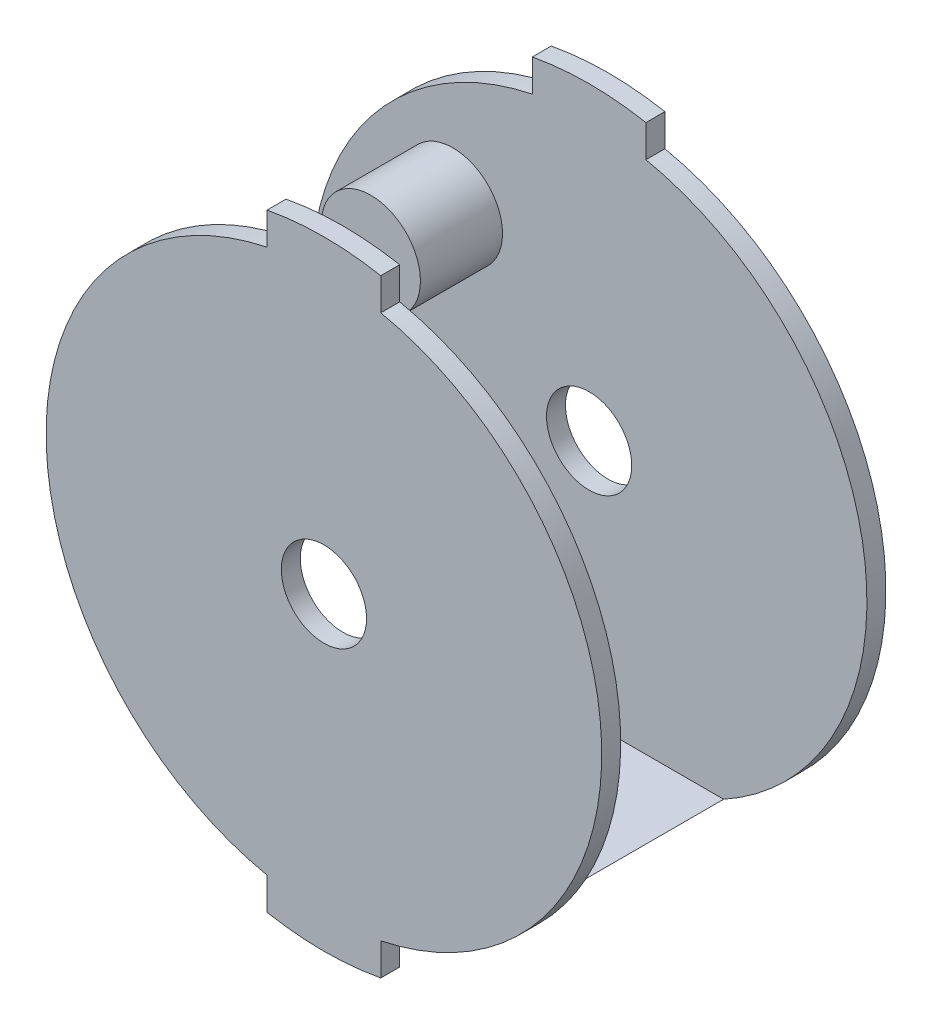
SolidWorks part; units mm, degrees
ref_plane "Front Plane" through (0, 0, 0) normal (0, 0, 1) x (1, 0, 0)
ref_plane "Top Plane" through (0, 0, 0) normal (0, 1, 0) x (1, 0, 0)
ref_plane "Right Plane" through (0, 0, 0) normal (1, 0, 0) x (0, 0, -1)
sketch "Sketch1" plane through (0, 0, 0) normal (0, 0, 1) x (1, 0, 0)
  line L0 (-2.286, 12.2343) -> (-2.286, 10.9397)
  line L1 (2.286, 12.2343) -> (2.286, 10.9397)
  line L2 (2.286, 12.2343) -> (-2.286, -12.2343) construction
  line L3 (-2.286, -10.9397) -> (-2.286, -12.2343)
  line L4 (2.286, -10.9397) -> (2.286, -12.2343)
  arc A0 (2.286, -10.9397) -> (2.286, 10.9397) centre (0, 0) ccw
  circle A1 centre (0, 0) radius 1.7145
  arc A2 (-2.286, -12.2343) -> (2.286, -12.2343) centre (0, 0) ccw
  arc A3 (2.286, 12.2343) -> (-2.286, 12.2343) centre (0, 0) ccw
  arc A4 (-2.286, 10.9397) -> (-2.286, -10.9397) centre (0, 0) ccw
  dimension "D1" = 22.352
  dimension "D2" = 3.429
  dimension "D3" = 4.572
  dimension "D4" = 24.892
extrude "Boss-Extrude1" add sketch "Sketch1" along normal blind 11.43
sketch "Sketch2" plane through (0, 0, 0) normal (1, 0, 0) x (0, 0, -1)
  line L0 (-11.43, 1.7145) -> (-11.43, -1.7145) construction
  line L1 (-10.668, 11.176) -> (-0.762, 11.176)
  line L2 (-10.668, 11.176) -> (-10.668, 13.716)
  line L3 (-10.668, 13.716) -> (-0.762, 13.716)
  line L4 (-0.762, 11.176) -> (-0.762, 13.716)
  line L5 (-10.668, 11.176) -> (-0.762, 13.716) construction
  line L6 (-10.668, 13.716) -> (-0.762, 11.176) construction
  point P0 (-5.715, 12.446)
  dimension "D1" = 11.176
  dimension "D2" = 0.762
  dimension "D3" = 0.762
  dimension "D4" = 2.54
ref_axis "Axis1" through (0, 0, 11.43) along (0, 0, -1)
revolve "Cut-Revolve1" cut sketch "Sketch2" angle 360 about axis through (0, 0, 11.43) along (0, 0, -1)
sketch "Sketch4" plane through (0, 0, 0) normal (1, 0, 0) x (0, 0, -1)
  line L0 (-0.762, 11.176) -> (-10.668, 11.176) construction
  line L1 (-0.762, 11.176) -> (-10.668, 11.176)
  line L2 (-0.762, 11.176) -> (-0.762, -9.779)
  line L3 (-0.762, -9.779) -> (-10.668, -9.779)
  line L4 (-10.668, 11.176) -> (-10.668, -9.779)
  line L6 (-10.668, 10.9397) -> (-10.668, 11.176) construction
  line L7 (-0.762, 11.176) -> (-0.762, 10.9397) construction
  line L8 (-0.762, -10.9397) -> (-0.762, -11.176) construction
  line L9 (-0.762, -11.176) -> (-10.668, -11.176)
  line L10 (-0.762, -11.176) -> (-0.762, -10.541)
  line L11 (-0.762, -10.541) -> (-10.668, -10.541)
  line L12 (-10.668, -11.176) -> (-10.668, -10.541)
  dimension "D1" = 20.955
  dimension "D2" = 0.635
extrude "Cut-Extrude1" cut sketch "Sketch4" against normal through all and the other way through all
sketch "Sketch3" plane through (0, 0, 0) normal (0, 0, 1) x (1, 0, 0)
  line L0 (0, 0) -> (-6.8879, 6.8879) construction
  line L1 (0, 0) -> (-17.0892, 0) construction
  circle A0 centre (-5.478, 5.478) radius 1.9939
  dimension "D1" = 3.9878
  dimension "D2" = 7.747
  dimension "D3" = 17.0892
  dimension "D4" = 45
extrude "Boss-Extrude2" add sketch "Sketch3" along normal blind 4.064
